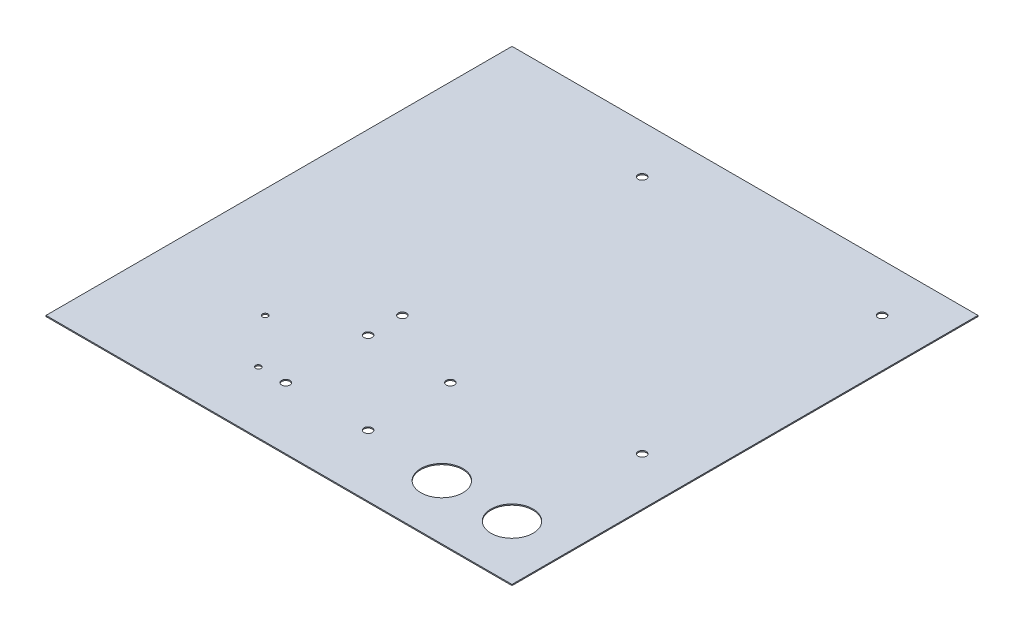
SolidWorks part; units mm, degrees
material "6061 Alloy"
ref_plane "Front Plane" through (0, 0, 0) normal (0, 0, 1) x (1, 0, 0)
ref_plane "Top Plane" through (0, 0, 0) normal (0, 1, 0) x (1, 0, 0)
ref_plane "Right Plane" through (0, 0, 0) normal (1, 0, 0) x (0, 0, -1)
sketch "Sketch1" plane through (0, 0, 0) normal (0, 0, 1) x (1, 0, 0)
  line L0 (0, 0.2032) -> (0, -0.2032)
  line L1 (-86.36, 0) -> (86.36, 0) construction
  point P6 (0, 0)
  dimension "Width" = 172.72
  dimension "Thk" = 0.4064
sketch "Sketch2" plane through (0, 0, 0) normal (1, 0, 0) x (0, 0, -1)
  line L0 (86.36, 0) -> (-86.36, 0)
  point P4 (0, 0)
  dimension "Length" = 172.72
sketch "Sketch3" plane through (0, 0, 0) normal (0, 0, 1) x (1, 0, 0)
  line L1 (86.36, 0.2032) -> (-86.36, 0.2032)
  line L2 (86.36, 0.2032) -> (86.36, -0.2032)
  line L3 (86.36, -0.2032) -> (-86.36, -0.2032)
  line L4 (-86.36, 0.2032) -> (-86.36, -0.2032)
  line L5 (86.36, 0.2032) -> (-86.36, -0.2032) construction
  line L6 (86.36, -0.2032) -> (-86.36, 0.2032) construction
  point P0 (0, 0)
extrude "Boss-Extrude1" add sketch "Sketch3" along normal up to vertex (86.36 mm away) and the other way up to vertex (86.36 mm away) up to point (0, 0, 86.36) other way up to point (0, 0, -86.36)
sketch "Sketch4" plane through (0, 0.2032, 0) normal (0, 1, 0) x (1, 0, 0)
  line L0 (86.36, -86.36) -> (86.36, 86.36) construction
  line L1 (86.36, -86.36) -> (-86.36, -86.36) construction
  circle A0 centre (40.04, -66.04) radius 7.8
  circle A1 centre (66.04, -66.04) radius 7.8
  dimension "D2" = 15.6
  dimension "D1" = 26
  dimension "D3" = 20.32
  dimension "D4" = 20.32
extrude "Cut-Extrude1" cut sketch "Sketch4" against normal through all
sketch "Sketch6" plane through (0, -0.2032, 0) normal (0, -1, 0) x (1, 0, 0)
  line L0 (86.36, 86.36) -> (86.36, -86.36) construction
  circle A0 centre (-20.32, 20.32) radius 1.524
  circle A1 centre (68.58, 20.32) radius 1.524
  circle A2 centre (68.58, -68.58) radius 1.524
  circle A3 centre (-20.32, -68.58) radius 1.524
  circle A4 centre (-20.32, 33.02) radius 1.524
  circle A5 centre (-20.32, 63.5203) radius 1.524
  circle A6 centre (10.1803, 63.5203) radius 1.524
  circle A7 centre (10.1803, 33.02) radius 1.524
  circle A8 centre (-45.72, 45.7403) radius 1
  circle A9 centre (-30.48, 63.5203) radius 1
  point P22 (-45.72, 63.5203)
  point P23 (0, 0)
  point P24 (0, 0)
  point P25 (0, 0)
  point P26 (-27.0127, 62.0528)
  point P27 (0, 0)
  dimension "D1" = 3.048
  dimension "D2" = 88.9
  dimension "D5" = 88.9
  dimension "D6" = 12.7
  dimension "D7" = 17.78
  dimension "D8" = 25.4
  dimension "D9" = 23.4176
  dimension "D10" = 15.24
  dimension "D11" = 17.78
  dimension "D3" = 2
  dimension "D4" = 2
extrude "Cut-Extrude2" cut sketch "Sketch6" against normal through all
